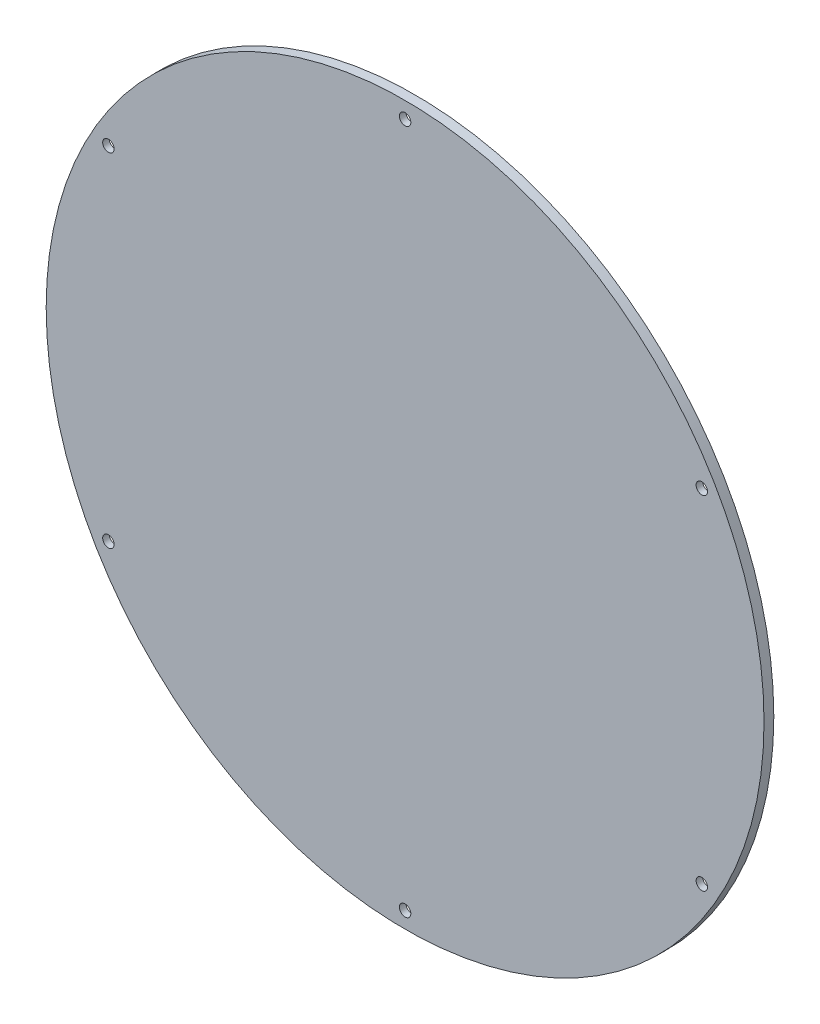
SolidWorks part; units mm, degrees
material "2024-O"
ref_plane "Alzado" through (0, 0, 0) normal (0, 0, 1) x (1, 0, 0)
ref_plane "Planta" through (0, 0, 0) normal (0, 1, 0) x (1, 0, 0)
ref_plane "Vista lateral" through (0, 0, 0) normal (1, 0, 0) x (0, 0, -1)
sketch "Croquis1" plane through (0, 0, 0) normal (0, 0, 1) x (1, 0, 0)
  circle A0 centre (0, 0) radius 110
  circle A1 centre (0, 105) radius 1.75
  circle A2 centre (90.9327, 52.5) radius 1.75
  circle A3 centre (90.9327, -52.5) radius 1.75
  circle A4 centre (0, -105) radius 1.75
  circle A5 centre (-90.9327, -52.5) radius 1.75
  circle A6 centre (-90.9327, 52.5) radius 1.75
  point P18 (0, 0)
  dimension "D1" = 220
  dimension "D2" = 3.5
  dimension "D3" = 105
  dimension "D4" = 6
extrude "Saliente-Extruir1" add sketch "Croquis1" along normal blind 3
chamfer "Chaflán1" distance 1 angle 60 1 edges at (1.75, 105, 0)
chamfer "Chaflán2" distance 1 angle 60 5 edges at (-89.1827, 52.5, 0) (-89.1827, -52.5, 0) (1.75, -105, 0) (92.6827, -52.5, 0) (92.6827, 52.5, 0)
